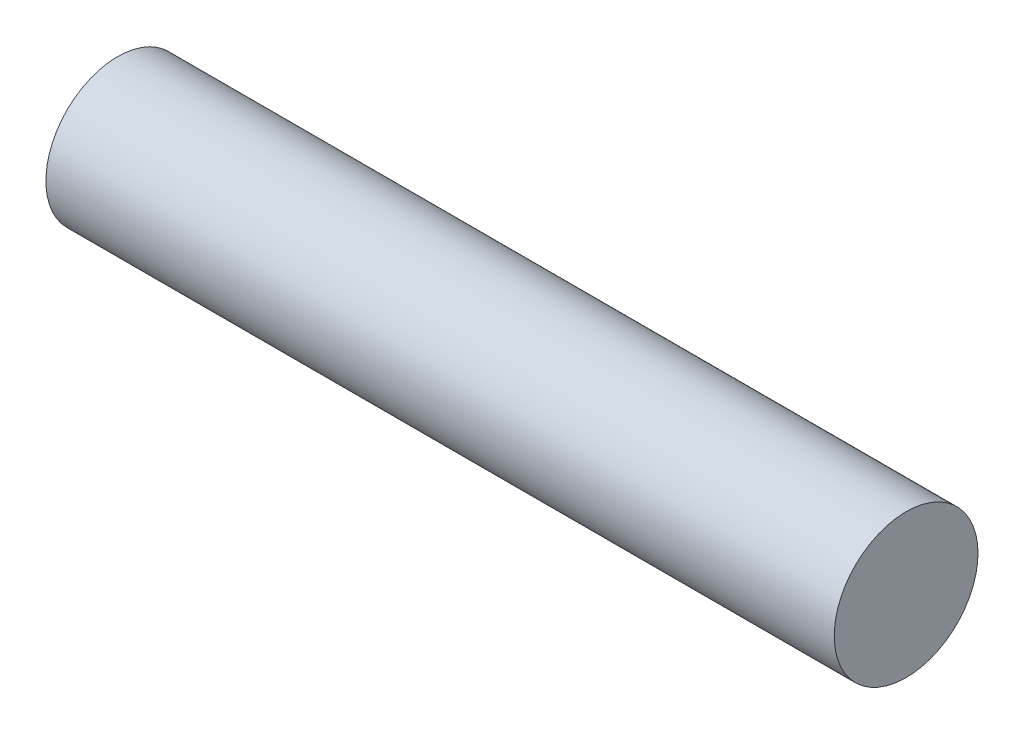
SolidWorks part; units mm, degrees
material "Cast Alloy Steel"
ref_plane "Front Plane" through (0, 0, 0) normal (0, 0, 1) x (1, 0, 0)
ref_plane "Top Plane" through (0, 0, 0) normal (0, 1, 0) x (1, 0, 0)
ref_plane "Right Plane" through (0, 0, 0) normal (1, 0, 0) x (0, 0, -1)
sketch "Sketch1" plane through (0, 0, 0) normal (1, 0, 0) x (0, 0, -1)
  circle A0 centre (0, 0) radius 37.8
  dimension "D1" = 75.6
extrude "Boss-Extrude1" add sketch "Sketch1" along normal mid plane 414.5
